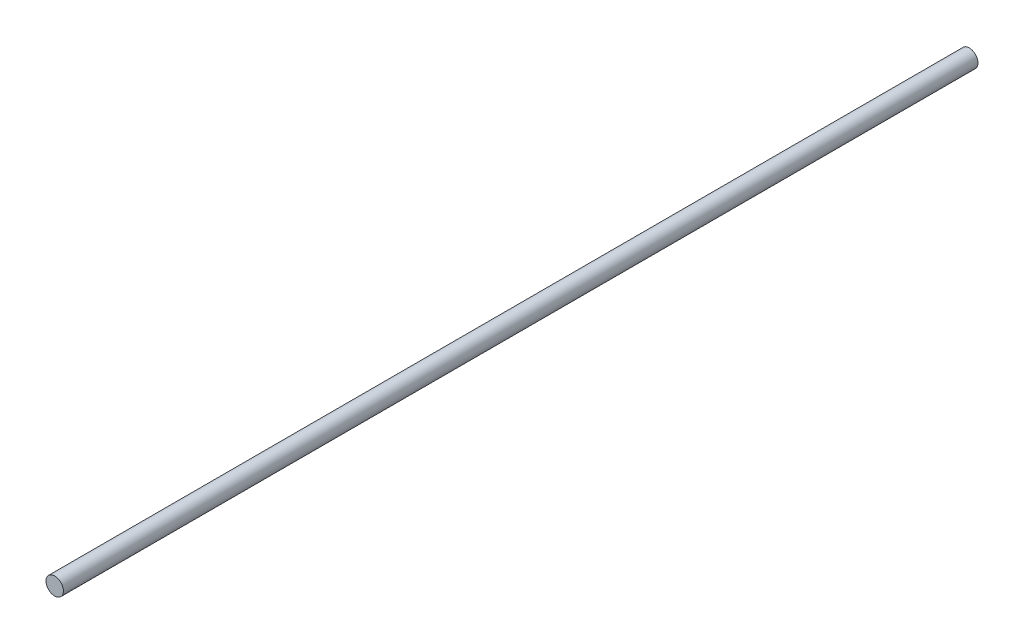
SolidWorks part; units mm, degrees
ref_plane "前视基准面" through (0, 0, 0) normal (0, 0, 1) x (1, 0, 0)
ref_plane "上视基准面" through (0, 0, 0) normal (0, 1, 0) x (1, 0, 0)
ref_plane "右视基准面" through (0, 0, 0) normal (1, 0, 0) x (0, 0, -1)
sketch "草图1" plane through (0, 0, 0) normal (0, 0, 1) x (1, 0, 0)
  circle A0 centre (-12.3857, 7.8929) radius 4
extrude "凸台-拉伸1" add sketch "草图1" along normal blind 420
